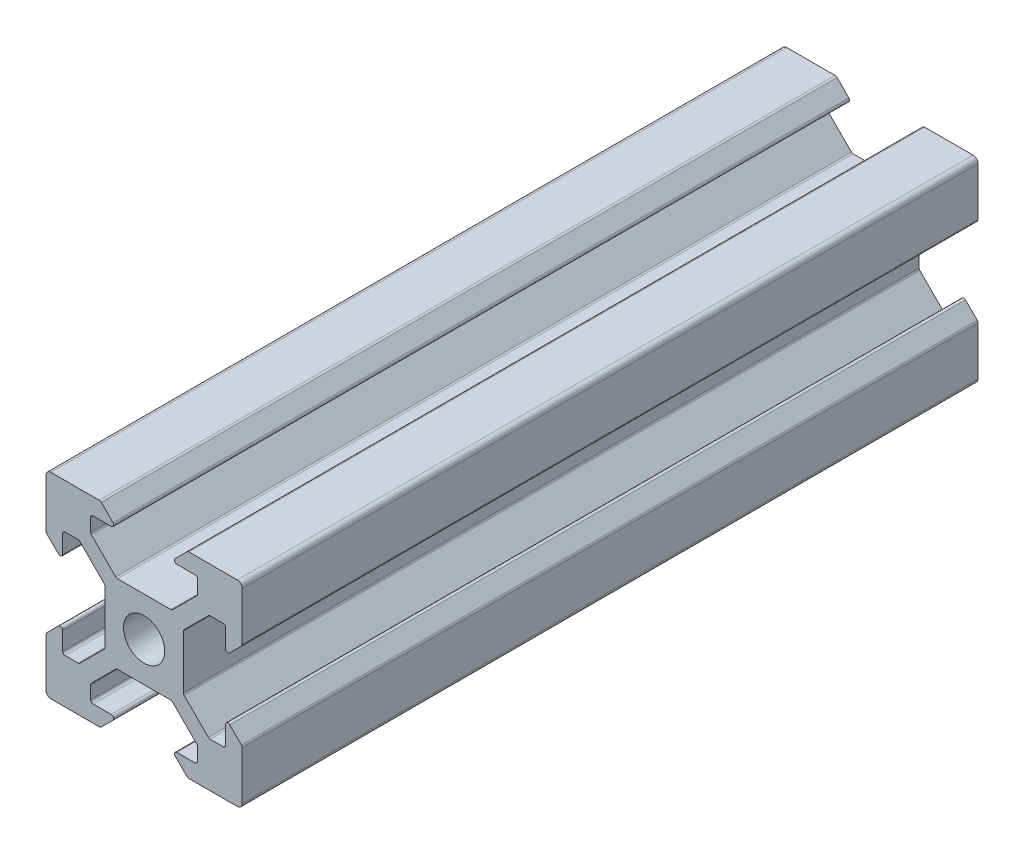
SolidWorks part; units mm, degrees
material "1060 Alloy"
ref_plane "Front Plane" through (0, 0, 0) normal (0, 0, 1) x (1, 0, 0)
ref_plane "Top Plane" through (0, 0, 0) normal (0, 1, 0) x (1, 0, 0)
ref_plane "Right Plane" through (0, 0, 0) normal (1, 0, 0) x (0, 0, -1)
sketch "Model" plane through (0, 0, 0) normal (0, 0, 1) x (1, 0, 0)
  line L0 (2012.9312, 1381.8004) -> (2012.9312, 1378.2004)
  line L1 (2016.4702, 1376.0004) -> (2017.3922, 1376.0004)
  line L2 (2020.9312, 1380.4614) -> (2020.9312, 1379.5394)
  line L3 (2016.4702, 1384.0004) -> (2017.3922, 1384.0004)
  line L270 (2012.9312, 1381.8004) -> (2012.9312, 1382.7004)
  line L271 (2012.8433, 1382.9125) -> (2010.3787, 1385.3772)
  line L272 (2010.2019, 1385.4504) -> (2008.8812, 1385.4504)
  line L273 (2008.6312, 1385.2004) -> (2008.6312, 1383.3504)
  line L274 (2008.2044, 1383.1736) -> (2007.0191, 1384.359)
  line L275 (2006.9312, 1384.5711) -> (2006.9312, 1389.5004)
  line L276 (2007.4312, 1390.0004) -> (2012.3605, 1390.0004)
  line L277 (2012.5726, 1389.9125) -> (2013.758, 1388.7272)
  line L278 (2013.5812, 1388.3004) -> (2011.7312, 1388.3004)
  line L279 (2011.4812, 1388.0504) -> (2011.4812, 1386.7297)
  line L280 (2011.5544, 1386.5529) -> (2014.0338, 1384.0736)
  line L281 (2014.2105, 1384.0004) -> (2016.4702, 1384.0004)
  line L282 (2017.3922, 1384.0004) -> (2019.6519, 1384.0004)
  line L283 (2019.8287, 1384.0736) -> (2022.308, 1386.5529)
  line L284 (2022.3812, 1386.7297) -> (2022.3812, 1388.0504)
  line L285 (2022.1312, 1388.3004) -> (2020.2812, 1388.3004)
  line L286 (2020.1044, 1388.7272) -> (2021.2898, 1389.9125)
  line L287 (2021.5019, 1390.0004) -> (2026.4312, 1390.0004)
  line L288 (2026.9312, 1389.5004) -> (2026.9312, 1384.5711)
  line L289 (2026.8433, 1384.359) -> (2025.658, 1383.1736)
  line L290 (2025.2312, 1383.3504) -> (2025.2312, 1385.2004)
  line L291 (2024.9812, 1385.4504) -> (2023.6605, 1385.4504)
  line L292 (2023.4838, 1385.3772) -> (2021.0044, 1382.8978)
  line L293 (2020.9312, 1382.7211) -> (2020.9312, 1380.4614)
  line L294 (2020.9312, 1379.5394) -> (2020.9312, 1377.2797)
  line L295 (2021.0044, 1377.1029) -> (2023.4838, 1374.6236)
  line L296 (2023.6605, 1374.5504) -> (2024.9812, 1374.5504)
  line L297 (2025.2312, 1374.8004) -> (2025.2312, 1376.6504)
  line L298 (2025.658, 1376.8272) -> (2026.8433, 1375.6418)
  line L299 (2026.9312, 1375.4297) -> (2026.9312, 1370.5004)
  line L300 (2026.4312, 1370.0004) -> (2021.5019, 1370.0004)
  line L301 (2021.2898, 1370.0883) -> (2020.1044, 1371.2736)
  line L302 (2020.2812, 1371.7004) -> (2022.1312, 1371.7004)
  line L303 (2022.3812, 1371.9504) -> (2022.3812, 1373.2711)
  line L304 (2022.308, 1373.4478) -> (2019.8287, 1375.9272)
  line L305 (2019.6519, 1376.0004) -> (2017.3922, 1376.0004)
  line L306 (2016.4702, 1376.0004) -> (2014.2105, 1376.0004)
  line L307 (2014.0338, 1375.9272) -> (2011.5544, 1373.4478)
  line L308 (2011.4812, 1373.2711) -> (2011.4812, 1371.9504)
  line L309 (2011.7312, 1371.7004) -> (2013.5812, 1371.7004)
  line L310 (2013.758, 1371.2736) -> (2012.5726, 1370.0883)
  line L311 (2012.3605, 1370.0004) -> (2007.4312, 1370.0004)
  line L312 (2006.9312, 1370.5004) -> (2006.9312, 1375.4297)
  line L313 (2007.0191, 1375.6418) -> (2008.2044, 1376.8272)
  line L314 (2008.6312, 1376.6504) -> (2008.6312, 1374.8004)
  line L315 (2008.8812, 1374.5504) -> (2010.2019, 1374.5504)
  line L316 (2010.3787, 1374.6236) -> (2012.8433, 1377.0883)
  line L317 (2012.9312, 1377.3004) -> (2012.9312, 1378.2004)
  circle A0 centre (2016.9312, 1380.0004) radius 2.1
  arc A427 (2012.9312, 1382.7004) -> (2012.8433, 1382.9125) centre (2012.6312, 1382.7004) ccw
  arc A428 (2010.3787, 1385.3772) -> (2010.2019, 1385.4504) centre (2010.2019, 1385.2004) ccw
  arc A429 (2008.8812, 1385.4504) -> (2008.6312, 1385.2004) centre (2008.8812, 1385.2004) ccw
  arc A430 (2008.2044, 1383.1736) -> (2008.6312, 1383.3504) centre (2008.3812, 1383.3504) ccw
  arc A431 (2006.9312, 1384.5711) -> (2007.0191, 1384.359) centre (2007.2312, 1384.5711) ccw
  arc A432 (2007.4312, 1390.0004) -> (2006.9312, 1389.5004) centre (2007.4312, 1389.5004) ccw
  arc A433 (2012.5726, 1389.9125) -> (2012.3605, 1390.0004) centre (2012.3605, 1389.7004) ccw
  arc A434 (2013.5812, 1388.3004) -> (2013.758, 1388.7272) centre (2013.5812, 1388.5504) ccw
  arc A435 (2011.7312, 1388.3004) -> (2011.4812, 1388.0504) centre (2011.7312, 1388.0504) ccw
  arc A436 (2011.4812, 1386.7297) -> (2011.5544, 1386.5529) centre (2011.7312, 1386.7297) ccw
  arc A437 (2014.0338, 1384.0736) -> (2014.2105, 1384.0004) centre (2014.2105, 1384.2504) ccw
  arc A441 (2019.6519, 1384.0004) -> (2019.8287, 1384.0736) centre (2019.6519, 1384.2504) ccw
  arc A442 (2022.308, 1386.5529) -> (2022.3812, 1386.7297) centre (2022.1312, 1386.7297) ccw
  arc A443 (2022.3812, 1388.0504) -> (2022.1312, 1388.3004) centre (2022.1312, 1388.0504) ccw
  arc A444 (2020.1044, 1388.7272) -> (2020.2812, 1388.3004) centre (2020.2812, 1388.5504) ccw
  arc A445 (2021.5019, 1390.0004) -> (2021.2898, 1389.9125) centre (2021.5019, 1389.7004) ccw
  arc A446 (2026.9312, 1389.5004) -> (2026.4312, 1390.0004) centre (2026.4312, 1389.5004) ccw
  arc A447 (2026.8433, 1384.359) -> (2026.9312, 1384.5711) centre (2026.6312, 1384.5711) ccw
  arc A448 (2025.2312, 1383.3504) -> (2025.658, 1383.1736) centre (2025.4812, 1383.3504) ccw
  arc A449 (2025.2312, 1385.2004) -> (2024.9812, 1385.4504) centre (2024.9812, 1385.2004) ccw
  arc A450 (2023.6605, 1385.4504) -> (2023.4838, 1385.3772) centre (2023.6605, 1385.2004) ccw
  arc A451 (2021.0044, 1382.8978) -> (2020.9312, 1382.7211) centre (2021.1812, 1382.7211) ccw
  arc A455 (2020.9312, 1377.2797) -> (2021.0044, 1377.1029) centre (2021.1812, 1377.2797) ccw
  arc A456 (2023.4838, 1374.6236) -> (2023.6605, 1374.5504) centre (2023.6605, 1374.8004) ccw
  arc A457 (2024.9812, 1374.5504) -> (2025.2312, 1374.8004) centre (2024.9812, 1374.8004) ccw
  arc A458 (2025.658, 1376.8272) -> (2025.2312, 1376.6504) centre (2025.4812, 1376.6504) ccw
  arc A459 (2026.9312, 1375.4297) -> (2026.8433, 1375.6418) centre (2026.6312, 1375.4297) ccw
  arc A460 (2026.4312, 1370.0004) -> (2026.9312, 1370.5004) centre (2026.4312, 1370.5004) ccw
  arc A461 (2021.2898, 1370.0883) -> (2021.5019, 1370.0004) centre (2021.5019, 1370.3004) ccw
  arc A462 (2020.2812, 1371.7004) -> (2020.1044, 1371.2736) centre (2020.2812, 1371.4504) ccw
  arc A463 (2022.1312, 1371.7004) -> (2022.3812, 1371.9504) centre (2022.1312, 1371.9504) ccw
  arc A464 (2022.3812, 1373.2711) -> (2022.308, 1373.4478) centre (2022.1312, 1373.2711) ccw
  arc A465 (2019.8287, 1375.9272) -> (2019.6519, 1376.0004) centre (2019.6519, 1375.7504) ccw
  arc A469 (2014.2105, 1376.0004) -> (2014.0338, 1375.9272) centre (2014.2105, 1375.7504) ccw
  arc A470 (2011.5544, 1373.4478) -> (2011.4812, 1373.2711) centre (2011.7312, 1373.2711) ccw
  arc A471 (2011.4812, 1371.9504) -> (2011.7312, 1371.7004) centre (2011.7312, 1371.9504) ccw
  arc A472 (2013.758, 1371.2736) -> (2013.5812, 1371.7004) centre (2013.5812, 1371.4504) ccw
  arc A473 (2012.3605, 1370.0004) -> (2012.5726, 1370.0883) centre (2012.3605, 1370.3004) ccw
  arc A474 (2006.9312, 1370.5004) -> (2007.4312, 1370.0004) centre (2007.4312, 1370.5004) ccw
  arc A475 (2007.0191, 1375.6418) -> (2006.9312, 1375.4297) centre (2007.2312, 1375.4297) ccw
  arc A476 (2008.6312, 1376.6504) -> (2008.2044, 1376.8272) centre (2008.3812, 1376.6504) ccw
  arc A477 (2008.6312, 1374.8004) -> (2008.8812, 1374.5504) centre (2008.8812, 1374.8004) ccw
  arc A478 (2010.2019, 1374.5504) -> (2010.3787, 1374.6236) centre (2010.2019, 1374.8004) ccw
  arc A479 (2012.8433, 1377.0883) -> (2012.9312, 1377.3004) centre (2012.6312, 1377.3004) ccw
extrude "Boss-Extrude1" add sketch "Model" along normal blind 75
